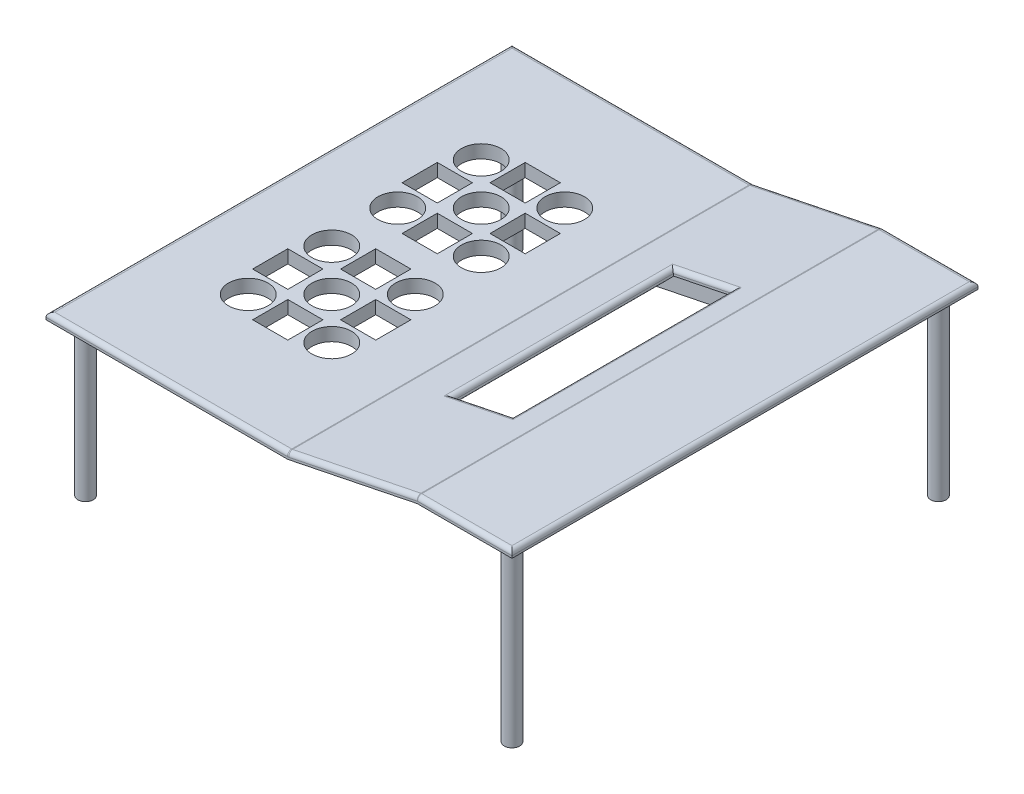
SolidWorks part; units mm, degrees
ref_plane "前视基准面" through (0, 0, 0) normal (0, 0, 1) x (1, 0, 0)
ref_plane "上视基准面" through (0, 0, 0) normal (0, 1, 0) x (1, 0, 0)
ref_plane "右视基准面" through (0, 0, 0) normal (1, 0, 0) x (0, 0, -1)
sketch "草图2" plane through (0, 0, 0) normal (0, 0, 1) x (1, 0, 0)
  line L0 (0, 0) -> (55, 0)
  line L1 (55, 0) -> (84.3939, 6)
  line L2 (84.3939, 6) -> (106, 6)
  line L3 (106, 6) -> (106, 4.5)
  line L4 (106, 4.5) -> (84.3939, 4.5)
  line L5 (84.3939, 4.5) -> (55, -1.5)
  line L6 (55, -1.5) -> (0, -1.5)
  line L7 (0, -1.5) -> (0, 0)
  line L8 (55, 0) -> (55, -1.5) construction
  line L9 (84.3939, 6) -> (84.3939, 4.5) construction
  point P5 (52.407, 5.0536)
  point P10 (79.3745, 8.2412)
  dimension "D1" = 30
  dimension "D2" = 1.5
  dimension "D3" = 106
  dimension "D4" = 55
  dimension "D5" = 6
extrude "凸台-拉伸1" add sketch "草图2" along normal blind 106
sketch "草图4" plane through (0, -1.5, 0) normal (0, -1, 0) x (1, 0, 0)
  line L0 (0, 106) -> (55, 106) construction
  line L1 (0, 106) -> (0, 0) construction
  circle A0 centre (4.5, 101.5) radius 1.75
  circle A1 centre (4.5, 101.5) radius 3 construction
  point P3 (4.2313, 102.2619)
  point P4 (4.6304, 101.5)
  dimension "D1" = 3.5
  dimension "D2" = 6
  dimension "D3" = 4.5
  dimension "D4" = 4.5
extrude "凸台-拉伸2" add sketch "草图4" along normal blind 34.6
sketch "草图5" plane through (0, 4.5, 0) normal (0, -1, 0) x (1, 0, 0)
  line L0 (84.3939, 106) -> (106, 106) construction
  line L1 (106, 106) -> (106, 0) construction
  circle A0 centre (101.5, 101.5) radius 1.75
  circle A1 centre (101.5, 101.5) radius 3 construction
  point P3 (97.1999, 101.3091)
  dimension "D1" = 6
  dimension "D2" = 3.5
  dimension "D3" = 4.5
  dimension "D4" = 4.5
extrude "凸台-拉伸3" add sketch "草图5" along normal blind 40.6
ref_plane "基准面1" through (0, 0, 53) normal (0, 0, 1) x (1, 0, 0)
mirror "镜向1" about plane through (0, 0, 53) normal (0, 0, 1) of "凸台-拉伸2", "凸台-拉伸3"
sketch "草图8" plane through (2.4939, -12.2178, 0) normal (0.2, -0.9798, 0) x (0.9798, 0.2, 0)
  line L0 (83.5888, 106) -> (83.5888, 0) construction
  line L1 (53.5888, 83) -> (83.5888, 83)
  line L2 (53.5888, 83) -> (53.5888, 23)
  line L3 (53.5888, 23) -> (83.5888, 23)
  line L4 (83.5888, 83) -> (83.5888, 23)
  line L5 (53.5888, 106) -> (53.5888, 0) construction
  line L6 (23.155, 53) -> (-23.155, 53) construction
  dimension "D1" = 60
  dimension "D2" = 30
extrude "凸台-拉伸4" add sketch "草图8" along normal blind 3.5
sketch "草图9" plane through (3.1939, -15.647, 0) normal (0.2, -0.9798, 0) x (0.9798, 0.2, 0)
  line L0 (23.155, 53) -> (-23.155, 53) construction
  line L1 (55.5888, 78.5) -> (81.5888, 78.5)
  line L2 (55.5888, 78.5) -> (55.5888, 27.5)
  line L3 (55.5888, 27.5) -> (81.5888, 27.5)
  line L4 (81.5888, 78.5) -> (81.5888, 27.5)
  line L5 (83.5888, 23) -> (83.5888, 83) construction
  dimension "D1" = 51
  dimension "D2" = 25.5
  dimension "D3" = 2
  dimension "D4" = 26
extrude "切除-拉伸1" cut sketch "草图9" against normal blind 1.5
sketch "草图10" plane through (2.8939, -14.1773, 0) normal (0.2, -0.9798, 0) x (0.9798, 0.2, 0)
  line L1 (60.5888, 78.5) -> (77.5888, 78.5)
  line L2 (60.5888, 78.5) -> (60.5888, 27.5)
  line L3 (60.5888, 27.5) -> (77.5888, 27.5)
  line L4 (77.5888, 78.5) -> (77.5888, 27.5)
  line L5 (23.155, 53) -> (-23.155, 53) construction
  line L6 (83.5888, 23) -> (83.5888, 83) construction
  dimension "D1" = 17
  dimension "D2" = 6
  dimension "D3" = 51
  dimension "D4" = 25.5
extrude "切除-拉伸2" cut sketch "草图10" against normal blind 2
sketch "草图11" plane through (2.2, -10.7778, 0) normal (-0.2, 0.9798, 0) x (0.9798, 0.2, 0)
  line L1 (63.5888, -28) -> (77.5888, -28)
  line L2 (63.5888, -28) -> (63.5888, -78)
  line L3 (63.5888, -78) -> (77.5888, -78)
  line L4 (77.5888, -28) -> (77.5888, -78)
  line L5 (-23.155, -53) -> (23.155, -53) construction
  line L10 (60.5888, -78.5) -> (77.5888, -78.5)
  line L11 (77.5888, -78.5) -> (77.5888, -27.5)
  line L12 (77.5888, -27.5) -> (60.5888, -27.5)
  line L13 (60.5888, -27.5) -> (60.5888, -78.5)
  line L14 (60.5888, -78.5) -> (77.5888, -78.5) construction
  line L15 (77.5888, -78.5) -> (77.5888, -27.5) construction
  line L16 (77.5888, -27.5) -> (60.5888, -27.5) construction
  line L17 (60.5888, -27.5) -> (60.5888, -78.5) construction
  dimension "D2" = 14
  dimension "D3" = 50
  dimension "D4" = 25
  dimension "D5" = 0
extrude "切除-拉伸4" cut sketch "草图11" against normal up to next
fillet "圆角3" radius 1 14 edges at (69.6969, 3, 106) (69.6969, 3, 0) (78.2212, 4.74, 53) (71.3626, 3.34, 28) (64.504, 1.94, 53) (71.3626, 3.34, 78) (106, 6, 53) (95.1969, 6, 106) (84.3939, 6, 53) (95.1969, 6, 0) (55, 0, 53) (27.5, 0, 106) (0, 0, 53) (27.5, 0, 0)
fillet "圆角4" radius 1 6 edges at (85.0939, 1.0707, 53) (55.7, -4.9293, 53) (70.3969, -1.9293, 23) (69.6969, 1.5, 23) (70.3969, -1.9293, 83) (69.6969, 1.5, 83)
sketch "草图13" plane through (0, -1.5, 0) normal (0, -1, 0) x (1, 0, 0)
  line L0 (0, 106) -> (0, 0) construction
  line L1 (2, 91) -> (53, 91)
  line L2 (2, 91) -> (2, 15)
  line L3 (2, 15) -> (53, 15)
  line L4 (53, 91) -> (53, 15)
  line L5 (55, 106) -> (55, 84) construction
  line L6 (23.155, 53) -> (-23.155, 53) construction
  dimension "D1" = 2
  dimension "D2" = 2
  dimension "D3" = 76
  dimension "D4" = 38
extrude "凸台-拉伸5" add sketch "草图13" along normal blind 3.5
sketch "草图14" plane through (0, -5, 0) normal (0, -1, 0) x (1, 0, 0)
  line L0 (53, 15) -> (53, 91) construction
  line L1 (3, 89) -> (53, 89)
  line L2 (3, 89) -> (3, 17)
  line L3 (3, 17) -> (53, 17)
  line L4 (53, 89) -> (53, 17)
  line L5 (2, 91) -> (2, 15) construction
  line L6 (23.155, 53) -> (-23.155, 53) construction
  dimension "D1" = 1
  dimension "D2" = 72
  dimension "D3" = 36
extrude "切除-拉伸5" cut sketch "草图14" against normal blind 2
sketch "草图15" plane through (0, 0, 0) normal (0, 1, 0) x (1, 0, 0)
  line L0 (-23.155, -53) -> (23.155, -53) construction
  line L1 (43, -32) -> (35, -32)
  line L2 (43, -32) -> (43, -40)
  line L3 (43, -40) -> (35, -40)
  line L4 (3, -89) -> (53, -89)
  line L5 (53, -89) -> (53, -17)
  line L6 (53, -17) -> (3, -17)
  line L7 (3, -17) -> (3, -89)
  line L8 (3, -89) -> (53, -89) construction
  line L9 (53, -89) -> (53, -17) construction
  line L10 (53, -17) -> (3, -17) construction
  line L11 (3, -17) -> (3, -89) construction
  line L12 (35, -32) -> (35, -40)
  line L13 (33, -22) -> (25, -22)
  line L14 (33, -22) -> (33, -30)
  line L15 (33, -30) -> (25, -30)
  line L16 (25, -22) -> (25, -30)
  line L17 (33, -42) -> (25, -42)
  line L18 (33, -42) -> (33, -50)
  line L19 (33, -50) -> (25, -50)
  line L20 (25, -42) -> (25, -50)
  line L21 (23, -32) -> (15, -32)
  line L22 (23, -32) -> (23, -40)
  line L23 (23, -40) -> (15, -40)
  line L24 (15, -32) -> (15, -40)
  circle A0 centre (29, -36) radius 4.5
  circle A1 centre (38.5, -26.5) radius 4.5
  circle A2 centre (38.5, -45.5) radius 4.5
  circle A3 centre (19.5, -26.5) radius 4.5
  circle A4 centre (19.5, -45.5) radius 4.5
  point P32 (0, 0)
  point P33 (0, 0)
  point P34 (0, 0)
  point P35 (41.1631, -22)
  point P36 (0, 0)
  dimension "D2" = 9
  dimension "D3" = 8
  dimension "D11" = 3
  dimension "D12" = 6
  dimension "D14" = 7.5
  dimension "D16" = 5.5
  dimension "D17" = 5.5
  dimension "D18" = 5.5
  dimension "D19" = 5.5
  dimension "D21" = 6
  dimension "D23" = 6
  dimension "D24" = 14.5
  dimension "D4" = 8
  dimension "D5" = 8
  dimension "D6" = 8
  dimension "D7" = 8
  dimension "D8" = 8
  dimension "D9" = 8
  dimension "D10" = 8
  dimension "D13" = 6
  dimension "D15" = 5.5
  dimension "D20" = 5.5
  dimension "D22" = 10
  dimension "D1" = 0
extrude "切除-拉伸7" cut sketch "草图15" against normal up to next
mirror "镜向2" about plane through (0, 0, 53) normal (0, 0, 1) of "切除-拉伸7"
